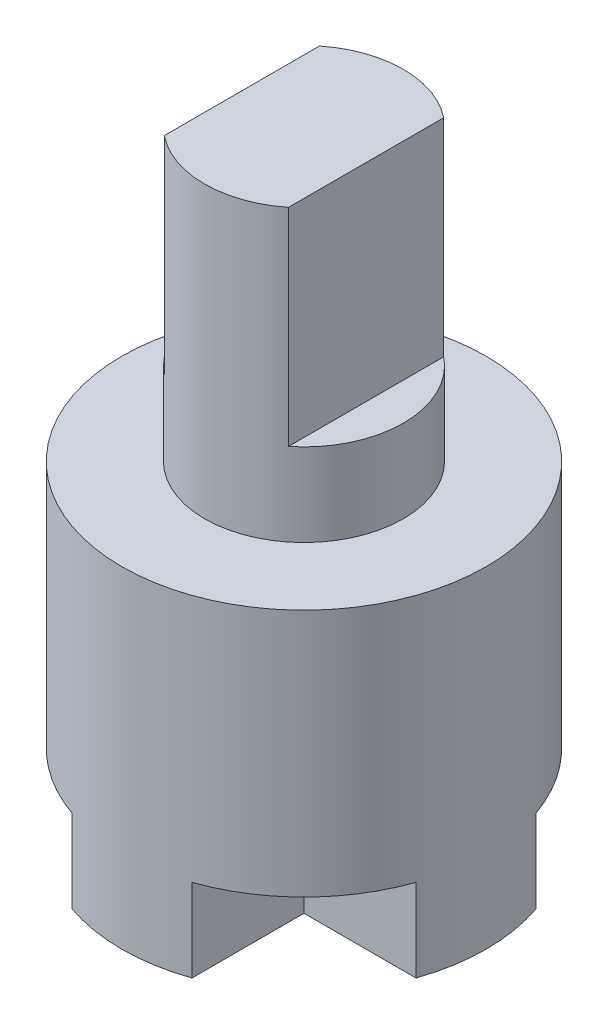
SolidWorks part; units mm, degrees
ref_plane "Front Plane" through (0, 0, 0) normal (0, 0, 1) x (1, 0, 0)
ref_plane "Top Plane" through (0, 0, 0) normal (0, 1, 0) x (1, 0, 0)
ref_plane "Right Plane" through (0, 0, 0) normal (1, 0, 0) x (0, 0, -1)
sketch "Sketch1" plane through (0, 0, 0) normal (0, 1, 0) x (1, 0, 0)
  circle A0 centre (0, 0) radius 4.4
extrude "Boss-Extrude1" add sketch "Sketch1" along normal blind 6
sketch "Sketch2" plane through (0, 6, 0) normal (0, 1, 0) x (1, 0, 0)
  circle A0 centre (0, 0) radius 2.4
  dimension "D1" = 4.8
extrude "Boss-Extrude2" add sketch "Sketch2" along normal blind 2
sketch "Sketch3" plane through (0, 8, 0) normal (0, 1, 0) x (1, 0, 0)
  line L2 (-1.5, -1.8735) -> (-1.5, 1.8735)
  line L4 (1.5, -1.8735) -> (1.5, 1.8735)
  line L5 (-1.1164, -2.1245) -> (1.1164, 2.1245) construction
  line L6 (-1.1164, 2.1245) -> (1.1164, -2.1245) construction
  circle A0 centre (0, 0) radius 2.4
  point P0 (0, 0)
  circle M6 centre (0, 0) radius 2.4
extrude "Boss-Extrude3" add sketch "Sketch3" along normal blind 5 contours L4 L2 M6
sketch "Sketch4" plane through (0, 0, 0) normal (0, -1, 0) x (1, 0, 0)
  line L1 (-4.1542, 1.45) -> (4.1542, 1.45)
  line L3 (-4.1542, -1.45) -> (4.1542, -1.45)
  line L5 (-4.2265, 1.2234) -> (4.2265, -1.2234) construction
  line L6 (-4.2265, -1.2234) -> (4.2265, 1.2234) construction
  line L8 (-1.45, 4.1542) -> (-1.45, -4.1542)
  line L10 (1.45, 4.1542) -> (1.45, -4.1542)
  line L11 (-1.3066, 4.2015) -> (1.3066, -4.2015) construction
  line L12 (-1.3066, -4.2015) -> (1.3066, 4.2015) construction
  circle A0 centre (0, 0) radius 4.4
  circle M3 centre (0, 0) radius 4.4
extrude "Boss-Extrude4" add sketch "Sketch4" along normal blind 2 contours L10 L3 L8 M3 | L10 L1 L8 L3 | L1 L10 L3 M3 | L8 L1 L3 M3 | L10 L8 L1 M3
